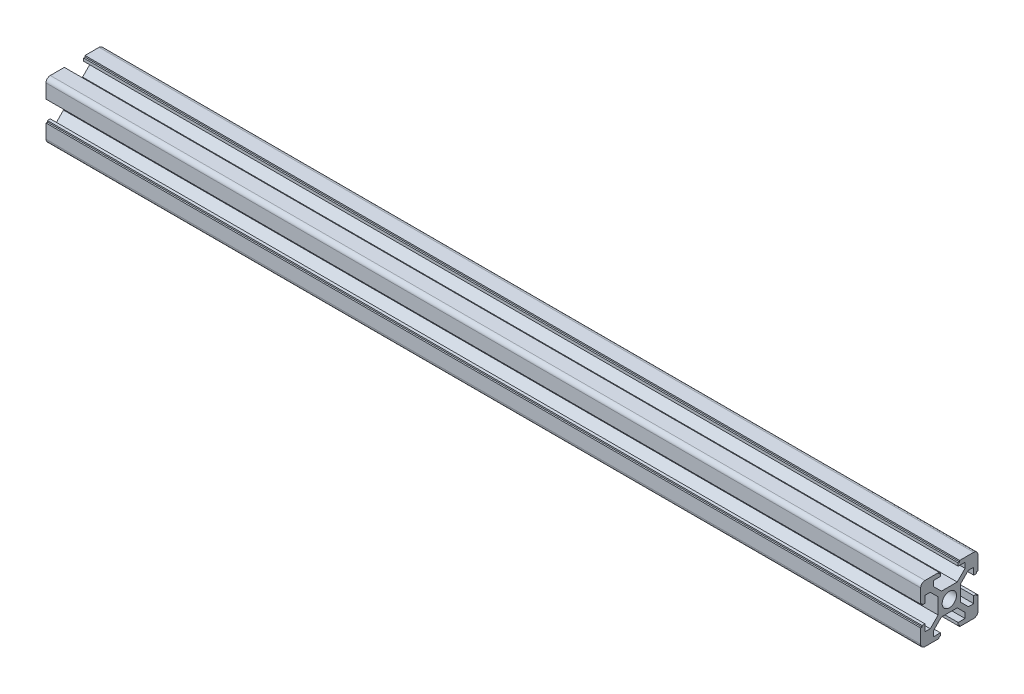
SolidWorks part; units mm, degrees
ref_plane "前视基准面" through (0, 0, 0) normal (0, 0, 1) x (1, 0, 0)
ref_plane "上视基准面" through (0, 0, 0) normal (0, 1, 0) x (1, 0, 0)
ref_plane "右视基准面" through (0, 0, 0) normal (1, 0, 0) x (0, 0, -1)
other "Configuration Table"
sketch "草图1" plane through (0, 0, 0) normal (0, 0, 1) x (1, 0, 0)
  line L0 (0, 0) -> (305, 0)
  dimension "D1" = 305
other "铝型材 20 X 20 X R1.5(1)"
ref_plane "基准面1" through (0, 0, 0) normal (1, 0, 0) x (0, 1, 0)
sketch "Sketch1" plane through (0, 0, 0) normal (1, 0, 0) x (0, 1, 0)
  line L0 (-3.6, 10) -> (-3.6, 9.5)
  line L1 (-3.6, 9.5) -> (-3.1, 9.5)
  line L2 (-3.1, 9.5) -> (-3.1, 8.5)
  line L3 (-3.1, 8.5) -> (-5.5, 8.5)
  line L4 (-8.5, -10) -> (-3.6, -10)
  line L5 (-10, -8.5) -> (-10, -3.6)
  line L6 (8.5, 10) -> (3.6, 10)
  line L7 (10, 8.5) -> (10, 3.6)
  line L8 (0, 14.8756) -> (0, 0) construction
  line L9 (0, 0) -> (14.1675, 0) construction
  line L10 (-5.5, 8.5) -> (-5.5, 6.65)
  line L11 (-5.5, 6.65) -> (-2.75, 3.9)
  line L12 (-2.75, 3.9) -> (2.75, 3.9)
  line L13 (5.5, 6.65) -> (2.75, 3.9)
  line L14 (5.5, 8.5) -> (5.5, 6.65)
  line L15 (3.1, 8.5) -> (5.5, 8.5)
  line L16 (3.1, 9.5) -> (3.1, 8.5)
  line L17 (3.6, 9.5) -> (3.1, 9.5)
  line L18 (3.6, 10) -> (3.6, 9.5)
  line L19 (-3.6, 10) -> (-8.5, 10)
  line L20 (10, 3.6) -> (9.5, 3.6)
  line L21 (9.5, 3.6) -> (9.5, 3.1)
  line L22 (9.5, 3.1) -> (8.5, 3.1)
  line L23 (8.5, 3.1) -> (8.5, 5.5)
  line L24 (8.5, 5.5) -> (6.65, 5.5)
  line L25 (6.65, 5.5) -> (3.9, 2.75)
  line L26 (3.9, 2.75) -> (3.9, -2.75)
  line L27 (6.65, -5.5) -> (3.9, -2.75)
  line L28 (8.5, -5.5) -> (6.65, -5.5)
  line L29 (8.5, -3.1) -> (8.5, -5.5)
  line L30 (9.5, -3.1) -> (8.5, -3.1)
  line L31 (9.5, -3.6) -> (9.5, -3.1)
  line L32 (10, -3.6) -> (9.5, -3.6)
  line L33 (3.6, -10) -> (3.6, -9.5)
  line L34 (3.6, -9.5) -> (3.1, -9.5)
  line L35 (3.1, -9.5) -> (3.1, -8.5)
  line L36 (3.1, -8.5) -> (5.5, -8.5)
  line L37 (5.5, -8.5) -> (5.5, -6.65)
  line L38 (5.5, -6.65) -> (2.75, -3.9)
  line L39 (2.75, -3.9) -> (-2.75, -3.9)
  line L40 (-5.5, -6.65) -> (-2.75, -3.9)
  line L41 (-5.5, -8.5) -> (-5.5, -6.65)
  line L42 (-3.1, -8.5) -> (-5.5, -8.5)
  line L43 (-3.1, -9.5) -> (-3.1, -8.5)
  line L44 (-3.6, -9.5) -> (-3.1, -9.5)
  line L45 (-3.6, -10) -> (-3.6, -9.5)
  line L46 (-10, -3.6) -> (-9.5, -3.6)
  line L47 (-9.5, -3.6) -> (-9.5, -3.1)
  line L48 (-9.5, -3.1) -> (-8.5, -3.1)
  line L49 (-8.5, -3.1) -> (-8.5, -5.5)
  line L50 (-8.5, -5.5) -> (-6.65, -5.5)
  line L51 (-6.65, -5.5) -> (-3.9, -2.75)
  line L52 (-3.9, -2.75) -> (-3.9, 2.75)
  line L53 (-6.65, 5.5) -> (-3.9, 2.75)
  line L54 (-8.5, 5.5) -> (-6.65, 5.5)
  line L55 (-8.5, 3.1) -> (-8.5, 5.5)
  line L56 (-9.5, 3.1) -> (-8.5, 3.1)
  line L57 (-9.5, 3.6) -> (-9.5, 3.1)
  line L58 (-10, 3.6) -> (-9.5, 3.6)
  line L59 (3.6, -10) -> (8.5, -10)
  line L60 (-10, 3.6) -> (-10, 8.5)
  line L61 (10, -3.6) -> (10, -8.5)
  circle A0 centre (0, 0) radius 2.5
  arc A1 (-10, 8.5) -> (-8.5, 10) centre (-8.5, 8.5) cw
  arc A2 (10, 8.5) -> (8.5, 10) centre (8.5, 8.5) ccw
  arc A3 (-8.5, -10) -> (-10, -8.5) centre (-8.5, -8.5) cw
  arc A4 (8.5, -10) -> (10, -8.5) centre (8.5, -8.5) ccw
  point P0 (-10, 0)
  point P1 (10, 0)
  point P2 (0, 10)
  point P3 (0, -10)
  point P4 (0, 0)
  point P5 (-10, -10)
  point P6 (10, -10)
  point P7 (10, 10)
  point P8 (-10, 10)
  point P13 (0, 0)
  point P36 (-10, 10)
  point P39 (10, 10)
  dimension "D1" = 11
  dimension "D2" = 20
  dimension "D3" = 6.2
  dimension "D4" = 7.2
  dimension "D5" = 6.1
  dimension "D6" = 5
  dimension "D7" = 1.5
  dimension "D8" = 45
  dimension "D9" = 0.5
  dimension "D10" = 1
  dimension "D11" = 5.5
